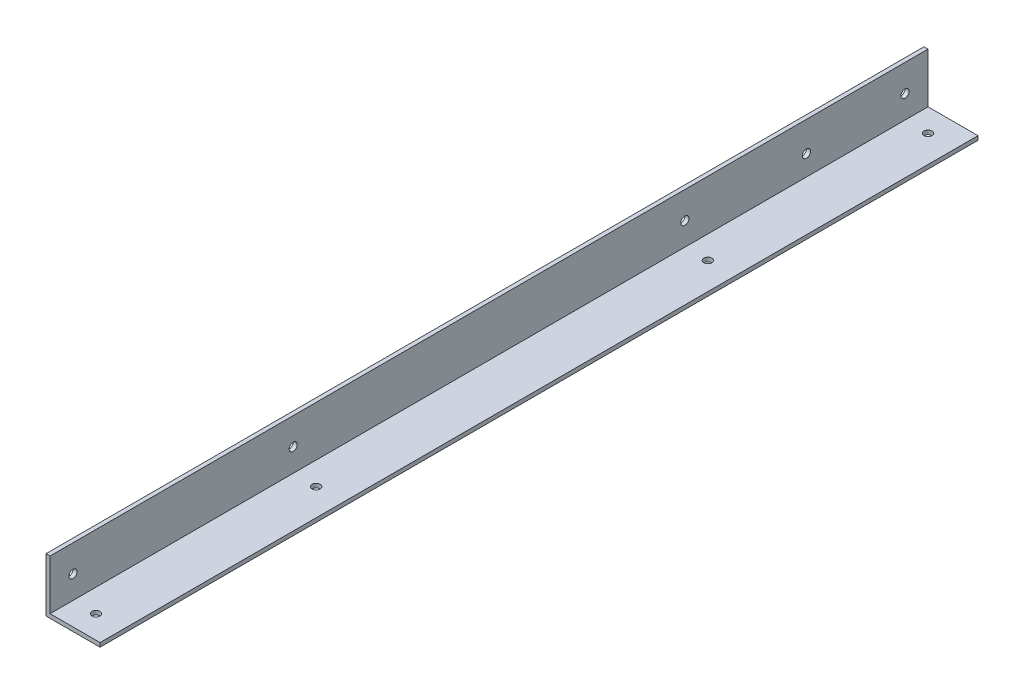
SolidWorks part; units mm, degrees
ref_plane "Plan de face" through (0, 0, 0) normal (0, 0, 1) x (1, 0, 0)
ref_plane "Plan de dessus" through (0, 0, 0) normal (0, 1, 0) x (1, 0, 0)
ref_plane "Plan de droite" through (0, 0, 0) normal (1, 0, 0) x (0, 0, -1)
sketch "Esquisse1" plane through (0, 0, 0) normal (0, 0, 1) x (1, 0, 0)
  line L0 (-17.4317, 4.7734) -> (-17.4317, -15.2266)
  line L1 (-17.4317, -15.2266) -> (2.5683, -15.2266)
  line L2 (2.5683, -15.2266) -> (2.5683, -13.7266)
  line L3 (2.5683, -13.7266) -> (-15.9317, -13.7266)
  line L4 (-15.9317, -13.7266) -> (-15.9317, 4.7734)
  line L5 (-15.9317, 4.7734) -> (-17.4317, 4.7734)
  dimension "D1" = 1.5
  dimension "D2" = 1.5
  dimension "D3" = 20
  dimension "D4" = 20
extrude "Extrusion1" add sketch "Esquisse1" along normal blind 325
sketch "Esquisse2" plane through (0, -13.7266, 0) normal (0, 1, 0) x (-1, 0, 0)
  line L0 (-2.5683, 325) -> (-2.5683, 0) construction
  line L1 (-2.5683, 325) -> (15.9317, 325) construction
  line L2 (-2.5683, 0) -> (15.9317, 0) construction
  circle A0 centre (7.4317, 8.5) radius 1.5
  circle A1 centre (7.4317, 316.5) radius 1.5
  circle A2 centre (7.4317, 235) radius 1.5
  circle A3 centre (7.4317, 90) radius 1.5
  dimension "D1" = 8.5
  dimension "D5" = 90
  dimension "D2" = 8.5
  dimension "D3" = 10
  dimension "D4" = 10
  dimension "D6" = 90
  dimension "D7" = 10
  dimension "D8" = 10
extrude "Extrusion2" cut sketch "Esquisse2" against normal blind 300
sketch "Esquisse3" plane through (-15.9317, 0, 0) normal (1, 0, 0) x (0, 0, -1)
  line L0 (-316.5, -5.2266) -> (-8.5, -5.2266) construction
  line L1 (-325, -13.7266) -> (-325, 4.7734) construction
  line L2 (0, -13.7266) -> (0, 4.7734) construction
  line L3 (-325, 4.7734) -> (0, 4.7734) construction
  line L5 (-325, -15.2266) -> (0, -15.2266) construction
  line L6 (0, 4.7734) -> (0, -15.2266) construction
  circle A0 centre (-316.5, -5.2266) radius 1.5
  circle A1 centre (-8.5, -5.2266) radius 1.5
  circle A2 centre (-235, -5.2266) radius 1.5
  circle A3 centre (-90, -5.2266) radius 1.5
  circle A4 centre (-45, -6.2266) radius 1.5
  point P14 (-325, -4.4766)
  dimension "D1" = 8.5
  dimension "D4" = 90
  dimension "D6" = 9
  dimension "D7" = 45
  dimension "D2" = 8.5
  dimension "D3" = 10
  dimension "D5" = 90
extrude "Extrusion3" cut sketch "Esquisse3" against normal blind 300
